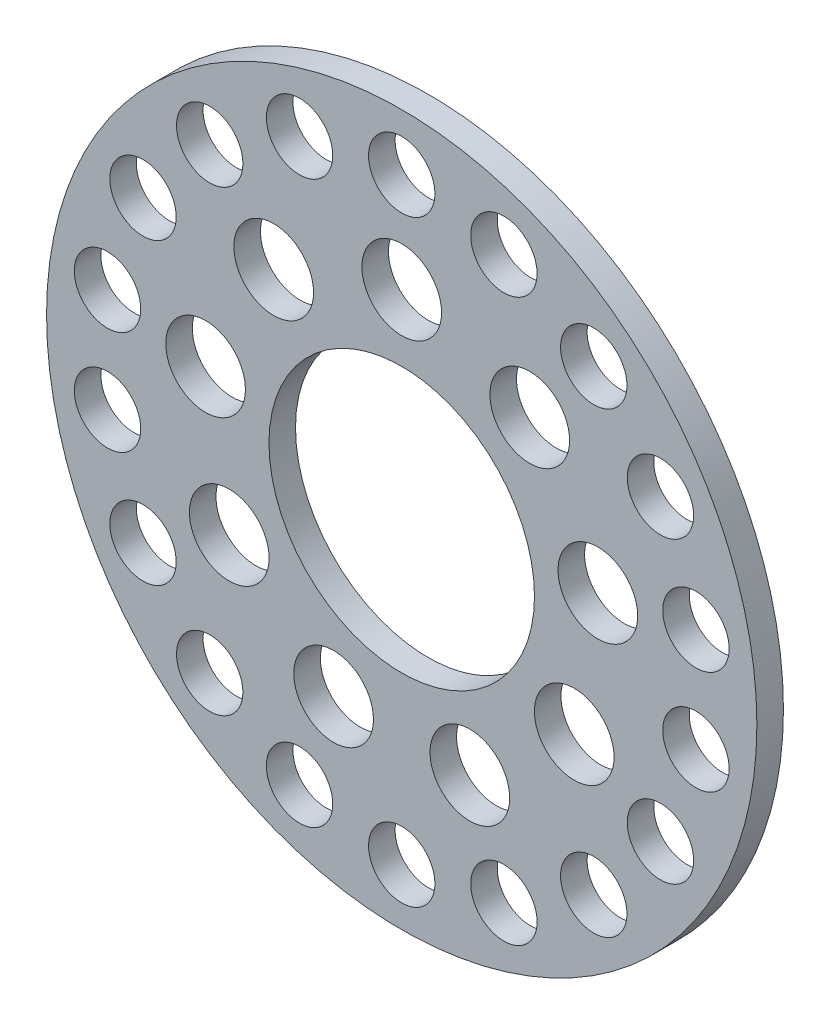
SolidWorks part; units mm, degrees
material "Thornel Mat VMA"
ref_plane "Front Plane" through (0, 0, 0) normal (0, 0, 1) x (1, 0, 0)
ref_plane "Top Plane" through (0, 0, 0) normal (0, 1, 0) x (1, 0, 0)
ref_plane "Right Plane" through (0, 0, 0) normal (1, 0, 0) x (0, 0, -1)
sketch "Sketch1" plane through (0, 0, 0) normal (0, 0, 1) x (1, 0, 0)
  line L0 (0, 0) -> (0, 32.2783) construction
  circle A0 centre (0, 0) radius 26.75
  circle A1 centre (0, 0) radius 10
  circle A2 centre (0, 22.5) radius 2.5
  circle A3 centre (7.6955, 21.1431) radius 2.5
  circle A4 centre (14.4627, 17.236) radius 2.5
  circle A5 centre (19.4856, 11.25) radius 2.5
  circle A6 centre (22.1582, 3.9071) radius 2.5
  circle A7 centre (22.1582, -3.9071) radius 2.5
  circle A8 centre (19.4856, -11.25) radius 2.5
  circle A9 centre (14.4627, -17.236) radius 2.5
  circle A10 centre (7.6955, -21.1431) radius 2.5
  circle A11 centre (0, -22.5) radius 2.5
  circle A12 centre (-7.6955, -21.1431) radius 2.5
  circle A13 centre (-14.4627, -17.236) radius 2.5
  circle A14 centre (-19.4856, -11.25) radius 2.5
  circle A15 centre (-22.1582, -3.9071) radius 2.5
  circle A16 centre (-22.1582, 3.9071) radius 2.5
  circle A17 centre (-19.4856, 11.25) radius 2.5
  circle A18 centre (-14.4627, 17.236) radius 2.5
  circle A19 centre (-7.6955, 21.1431) radius 2.5
  circle A20 centre (0, 15) radius 3
  circle A21 centre (9.6418, 11.4907) radius 3
  circle A22 centre (14.7721, 2.6047) radius 3
  circle A23 centre (12.9904, -7.5) radius 3
  circle A24 centre (5.1303, -14.0954) radius 3
  circle A25 centre (-5.1303, -14.0954) radius 3
  circle A26 centre (-12.9904, -7.5) radius 3
  circle A27 centre (-14.7721, 2.6047) radius 3
  circle A28 centre (-9.6418, 11.4907) radius 3
  point P42 (0, 0)
  point P61 (0, 0)
  dimension "D1" = 5
  dimension "D2" = 53.5
  dimension "D4" = 20
  dimension "D6" = 6
  dimension "D3" = 22.5
  dimension "D7" = 15
  dimension "D5" = 18
  dimension "D8" = 9
extrude "Boss-Extrude1" add sketch "Sketch1" along normal blind 2
